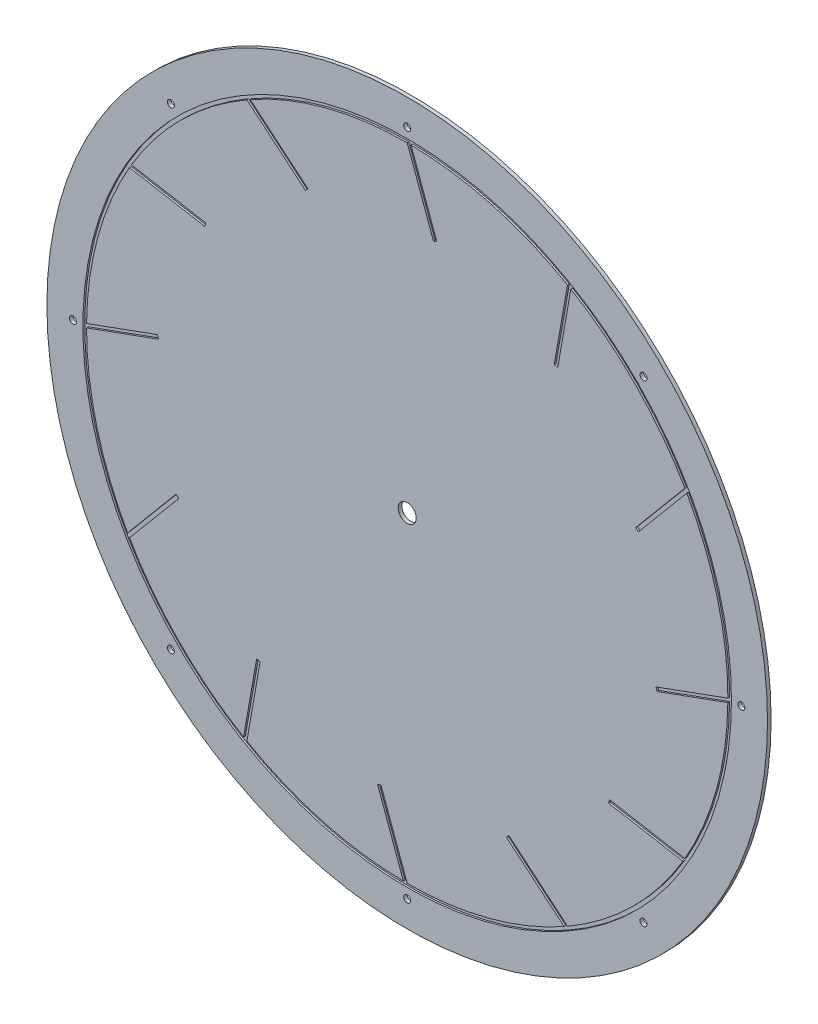
SolidWorks part; units mm, degrees
ref_plane "Front Plane" through (0, 0, 0) normal (0, 0, 1) x (1, 0, 0)
ref_plane "Top Plane" through (0, 0, 0) normal (0, 1, 0) x (1, 0, 0)
ref_plane "Right Plane" through (0, 0, 0) normal (1, 0, 0) x (0, 0, -1)
sketch "Sketch1" plane through (0, 0, 0) normal (0, 0, 1) x (1, 0, 0)
  circle A0 centre (0, 0) radius 254
  dimension "D1" = 508
extrude "Boss-Extrude1" add sketch "Sketch1" along normal blind 2.54
sketch "Sketch2" plane through (0, 0, 2.54) normal (0, 0, 1) x (1, 0, 0)
  circle A0 centre (0, 0) radius 228.6
  circle A1 centre (0, 0) radius 226.06
  dimension "D1" = 457.2
  dimension "D2" = 452.12
extrude "Cut-Extrude1" cut sketch "Sketch2" against normal blind 1.27
sketch "Sketch4" plane through (0, 0, 2.54) normal (0, 0, 1) x (1, 0, 0)
  line L0 (0, 0) -> (-286.1423, 0) construction
  line L1 (-226.06, 0) -> (-175.26, 18.4897)
  line L2 (-175.26, 18.4897) -> (-176.1287, 20.8765)
  line L3 (-176.1287, 20.8765) -> (-226.0438, 2.7089)
  line L4 (-195.7737, 113.03) -> (-142.5348, 103.6425)
  line L5 (-142.5348, 103.6425) -> (-142.0937, 106.144)
  line L6 (-142.0937, 106.144) -> (-194.4052, 115.3679)
  line L7 (-113.03, 195.7737) -> (-71.6175, 161.0245)
  line L8 (-71.6175, 161.0245) -> (-69.9848, 162.9702)
  line L9 (-69.9848, 162.9702) -> (-110.6759, 197.1141)
  line L10 (0, 226.06) -> (18.4897, 175.26)
  line L11 (18.4897, 175.26) -> (20.8765, 176.1287)
  line L12 (20.8765, 176.1287) -> (2.7089, 226.0438)
  line L13 (113.03, 195.7737) -> (103.6425, 142.5348)
  line L14 (103.6425, 142.5348) -> (106.144, 142.0937)
  line L15 (106.144, 142.0937) -> (115.3679, 194.4052)
  line L16 (195.7737, 113.03) -> (161.0245, 71.6175)
  line L17 (161.0245, 71.6175) -> (162.9702, 69.9848)
  line L18 (162.9702, 69.9848) -> (197.1141, 110.6759)
  line L19 (226.06, 0) -> (175.26, -18.4897)
  line L20 (175.26, -18.4897) -> (176.1287, -20.8765)
  line L21 (176.1287, -20.8765) -> (226.0438, -2.7089)
  line L22 (195.7737, -113.03) -> (142.5348, -103.6425)
  line L23 (142.5348, -103.6425) -> (142.0937, -106.144)
  line L24 (142.0937, -106.144) -> (194.4052, -115.3679)
  line L25 (113.03, -195.7737) -> (71.6175, -161.0245)
  line L26 (71.6175, -161.0245) -> (69.9848, -162.9702)
  line L27 (69.9848, -162.9702) -> (110.6759, -197.1141)
  line L28 (0, -226.06) -> (-18.4897, -175.26)
  line L29 (-18.4897, -175.26) -> (-20.8765, -176.1287)
  line L30 (-20.8765, -176.1287) -> (-2.7089, -226.0438)
  line L31 (-113.03, -195.7737) -> (-103.6425, -142.5348)
  line L32 (-103.6425, -142.5348) -> (-106.144, -142.0937)
  line L33 (-106.144, -142.0937) -> (-115.3679, -194.4052)
  line L34 (-195.7737, -113.03) -> (-161.0245, -71.6175)
  line L35 (-161.0245, -71.6175) -> (-162.9702, -69.9848)
  line L36 (-162.9702, -69.9848) -> (-197.1141, -110.6759)
  circle A0 centre (0, 0) radius 226.06 construction
  arc A1 (-226.0438, 2.7089) -> (-226.06, 0) centre (0, 0) ccw
  arc A2 (-194.4052, 115.3679) -> (-195.7737, 113.03) centre (0, 0) ccw
  arc A3 (-110.6759, 197.1141) -> (-113.03, 195.7737) centre (0, 0) ccw
  arc A4 (2.7089, 226.0438) -> (0, 226.06) centre (0, 0) ccw
  arc A5 (115.3679, 194.4052) -> (113.03, 195.7737) centre (0, 0) ccw
  arc A6 (197.1141, 110.6759) -> (195.7737, 113.03) centre (0, 0) ccw
  arc A7 (226.0438, -2.7089) -> (226.06, 0) centre (0, 0) ccw
  arc A8 (194.4052, -115.3679) -> (195.7737, -113.03) centre (0, 0) ccw
  arc A9 (110.6759, -197.1141) -> (113.03, -195.7737) centre (0, 0) ccw
  arc A10 (-2.7089, -226.0438) -> (0, -226.06) centre (0, 0) ccw
  arc A11 (-115.3679, -194.4052) -> (-113.03, -195.7737) centre (0, 0) ccw
  arc A12 (-197.1141, -110.6759) -> (-195.7737, -113.03) centre (0, 0) ccw
  dimension "D1" = 2.54
  dimension "D3" = 50.8
  dimension "D2" = 12
extrude "Cut-Extrude2" cut sketch "Sketch4" against normal blind 1.27
sketch "Sketch6" plane through (0, 0, 2.54) normal (0, 0, 1) x (1, 0, 0)
  line L0 (0, 0) -> (-426.7397, 0) construction
  circle A0 centre (-234.95, 0) radius 6.35
  circle A1 centre (0, 0) radius 228.6 construction
  circle A2 centre (-117.475, 203.4727) radius 6.35
  circle A3 centre (117.475, 203.4727) radius 6.35
  circle A4 centre (234.95, 0) radius 6.35
  circle A5 centre (117.475, -203.4727) radius 6.35
  circle A6 centre (-117.475, -203.4727) radius 6.35
  dimension "D1" = 12.7
  dimension "D2" = 6
extrude "Boss-Extrude2" [suppressed] add sketch "Sketch6" along normal blind 50.8
sketch "Sketch8" plane through (0, 0, 0) normal (0, 0, -1) x (-1, 0, 0)
  circle A0 centre (0, 0) radius 6.35
  dimension "D1" = 12.7
extrude "Cut-Extrude3" cut sketch "Sketch8" against normal through all
hole_wizard "#10 (0.1935) Diameter Hole1" positions "Sketch12" profile "Sketch11" hole size "#10" standard "ANSI Inch" end condition through all
sketch "Sketch12" plane through (0, 0, 2.54) normal (0, 0, 1) x (1, 0, 0)
  point P0 (-235.585, 0)
  point P18 (-166.5838, 166.5838)
  point P19 (0, 235.585)
  point P20 (166.5838, 166.5838)
  point P21 (235.585, 0)
  point P22 (166.5838, -166.5838)
  point P23 (0, -235.585)
  point P24 (-166.5838, -166.5838)
  dimension "D1" = 235.585
  dimension "D2" = 8
sketch "Sketch11" plane through (-235.585, 0, 2.54) normal (1, 0, 0) x (0, -1, 0)
  line L0 (0, 0) -> (0, 2.54)
  line L1 (0, 2.54) -> (2.4574, 2.54)
  line L2 (2.4574, 2.54) -> (2.4574, 0)
  line L5 (2.4574, 0) -> (0, 0)
  line L11 (0, -6.35) -> (0, 107.95) construction
  dimension "Thru Hole Dia." = 4.9149
  dimension "Thru Hole Depth" = 2.54
